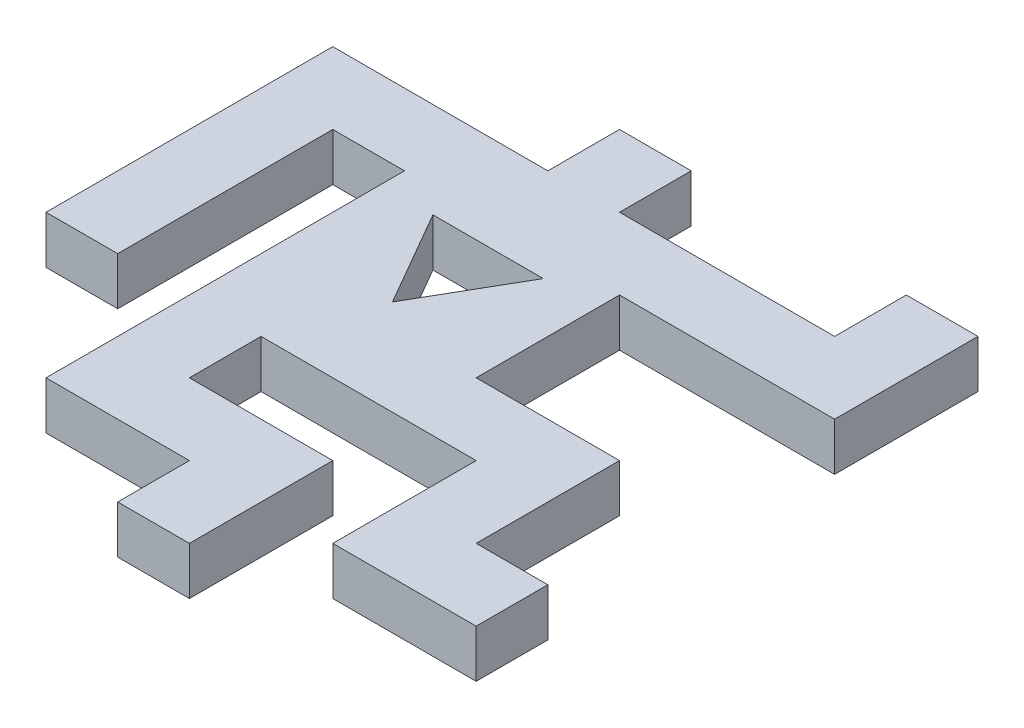
SolidWorks part; units mm, degrees
ref_plane "Front Plane" through (0, 0, 0) normal (0, 0, 1) x (1, 0, 0)
ref_plane "Top Plane" through (0, 0, 0) normal (0, 1, 0) x (1, 0, 0)
ref_plane "Right Plane" through (0, 0, 0) normal (1, 0, 0) x (0, 0, -1)
sketch "Sketch1" plane through (0, 0, 0) normal (0, 1, 0) x (1, 0, 0)
  line L0 (11.25, 15) -> (26.25, 15)
  line L1 (-11.25, 15) -> (11.25, 15)
  line L2 (-11.25, 15) -> (-11.25, -15)
  line L3 (-11.25, -15) -> (11.25, -15)
  line L4 (11.25, 15) -> (11.25, -15)
  line L5 (-11.25, 15) -> (11.25, -15) construction
  line L6 (-11.25, -15) -> (11.25, 15) construction
  line L7 (-3.75, 15) -> (3.75, 15)
  line L8 (-3.75, 15) -> (-3.75, 22.5)
  line L9 (-3.75, 22.5) -> (3.75, 22.5)
  line L10 (3.75, 15) -> (3.75, 22.5)
  line L11 (26.25, 15) -> (26.25, 22.5)
  line L12 (26.25, 22.5) -> (33.75, 22.5)
  line L13 (33.75, 22.5) -> (33.75, 7.5)
  line L14 (33.75, 7.5) -> (11.25, 7.5)
  line L15 (-11.25, 15) -> (-26.25, 15)
  line L16 (-26.25, 15) -> (-26.25, -15)
  line L17 (-26.25, -15) -> (-18.75, -15)
  line L18 (-18.75, -15) -> (-18.75, 7.5)
  line L19 (-18.75, 7.5) -> (-11.25, 7.5)
  line L20 (-11.25, -15) -> (-11.25, -30)
  line L21 (-11.25, -30) -> (3.75, -30)
  line L22 (3.75, -30) -> (3.75, -37.5)
  line L23 (3.75, -37.5) -> (11.25, -37.5)
  line L24 (11.25, -37.5) -> (11.25, -22.5)
  line L25 (11.25, -22.5) -> (-3.75, -22.5)
  line L26 (-3.75, -22.5) -> (-3.75, -15)
  line L27 (11.25, -7.5) -> (26.25, -7.5)
  line L28 (26.25, -7.5) -> (26.25, -22.5)
  line L29 (26.25, -22.5) -> (33.75, -22.5)
  line L30 (33.75, -22.5) -> (33.75, -30)
  line L31 (33.75, -30) -> (18.75, -30)
  line L32 (18.75, -30) -> (18.75, -15)
  line L33 (18.75, -15) -> (11.25, -15)
  point P0 (0, 0)
  dimension "D1" = 30
  dimension "D2" = 22.5
  dimension "D3" = 7.5
  dimension "D4" = 7.5
  dimension "D5" = 7.5
  dimension "D6" = 22.5
  dimension "D7" = 15
  dimension "D8" = 7.5
  dimension "D9" = 7.5
  dimension "D10" = 15
  dimension "D11" = 30
  dimension "D12" = 7.5
  dimension "D13" = 7.5
  dimension "D14" = 15
  dimension "D15" = 15
  dimension "D16" = 7.5
  dimension "D17" = 7.5
  dimension "D18" = 15
  dimension "D19" = 15
  dimension "D20" = 15
  dimension "D21" = 15
  dimension "D22" = 7.5
  dimension "D23" = 7.5
  dimension "D24" = 15
  dimension "D25" = 15
extrude "Boss-Extrude1" add sketch "Sketch1" along normal blind 5 contours L18 L19 L2 L15 L16 L17 | L4 L1 L2 L3 | L1 L10 L9 L8 | L14 L13 L12 L11 L0 L4 | L33 L32 L31 L30 L29 L28 L27 L4 | L25 L26 L3 L20 L21 L22 L23 L24
sketch "Sketch2" plane through (0, 5, 0) normal (0, 1, 0) x (1, 0, 0)
  line L0 (-11.25, 7.5) -> (11.25, 7.5) construction
  line L1 (11.25, -7.5) -> (-11.25, -7.5) construction
  line L2 (-11.25, 7.5) -> (-11.25, -30) construction
  line L3 (-5.7735, 5) -> (5.7735, 5)
  line L4 (5.7735, 5) -> (0, -5)
  line L5 (0, -5) -> (-5.7735, 5)
  dimension "D1" = 2.5
  dimension "D2" = 2.5
extrude "Cut-Extrude1" cut sketch "Sketch2" against normal through all
equation "\"Square Width\" = 7.5mm"
equation "\"Square Height\"= 7.5mm"
equation "\"Tolerance\"= 1mm"
equation "\"Block Height\" = 5mm"
equation "\"Base Height\"= 10mm"
equation "\"D1@Sketch1\"=\"Square Height\"*4"
equation "\"D2@Sketch1\"=\"Square Width\"*3"
equation "\"D3@Sketch1\"=\"Square Width\""
equation "\"D4@Sketch1\"=\"Square Height\""
equation "\"D5@Sketch1\"=\"Square Width\""
equation "\"D6@Sketch1\"=\"Square Width\"*3"
equation "\"D7@Sketch1\"=\"Square Width\"*2"
equation "\"D8@Sketch1\"=\"Square Height\""
equation "\"D9@Sketch1\"=\"Square Height\""
equation "\"D10@Sketch1\"=\"Square Width\"*2"
equation "\"D11@Sketch1\"=\"Square Height\"*4"
equation "\"D12@Sketch1\"=\"Square Height\""
equation "\"D13@Sketch1\"=\"Square Width\""
equation "\"D14@Sketch1\"=\"Square Height\"*2"
equation "\"D15@Sketch1\"=\"Square Width\"*2"
equation "\"D16@Sketch1\"=\"Square Height\""
equation "\"D17@Sketch1\"=\"Square Width\""
equation "\"D18@Sketch1\"=\"Square Height\"*2"
equation "\"D19@Sketch1\"=\"Square Width\"*2"
equation "\"D20@Sketch1\"=\"Square Width\"*2"
equation "\"D21@Sketch1\"=\"Square Height\"*2"
equation "\"D22@Sketch1\"=\"Square Width\""
equation "\"D23@Sketch1\"=\"Square Height\""
equation "\"D24@Sketch1\"=\"Square Width\"*2"
equation "\"D25@Sketch1\"=\"Square Height\"*2"
equation "\"D1@Boss-Extrude1\"=\"Block Height\""
equation "\"D1@Sketch2\"=\"Square Width\"/3"
equation "\"D2@Sketch2\"=\"Square Height\"/3"
